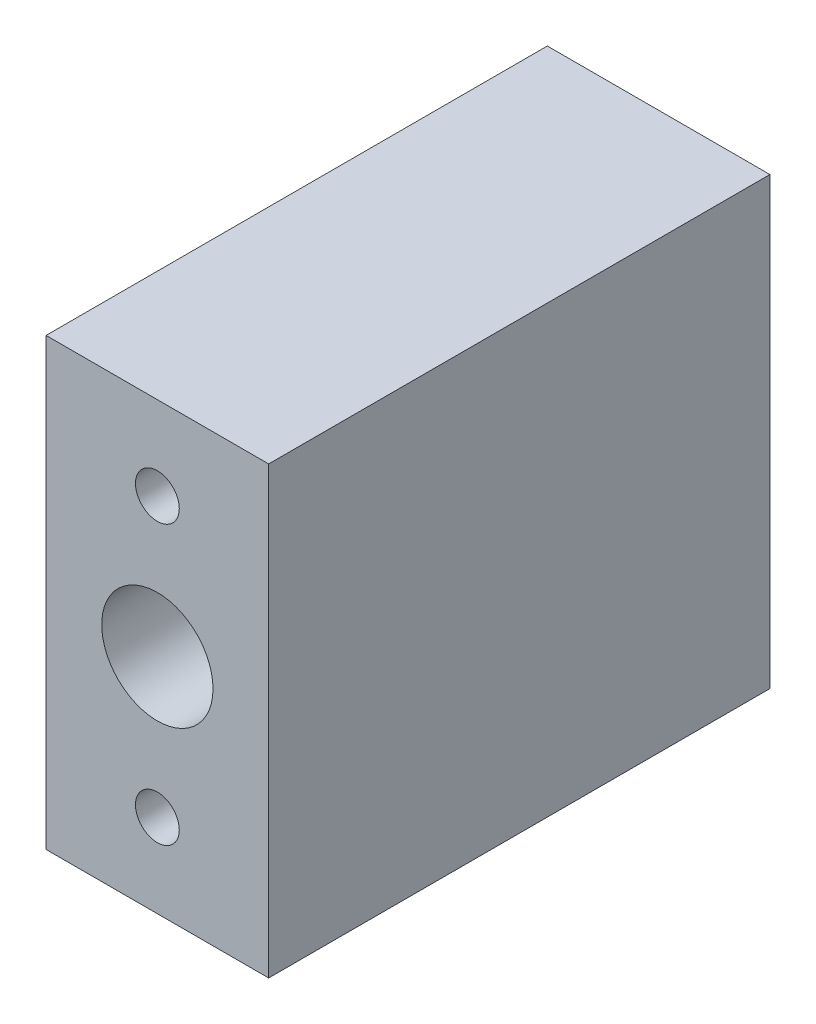
SolidWorks part; units mm, degrees
ref_plane "Front" through (0, 0, 0) normal (0, 0, 1) x (1, 0, 0)
ref_plane "Top" through (0, 0, 0) normal (0, 1, 0) x (1, 0, 0)
ref_plane "Right" through (0, 0, 0) normal (1, 0, 0) x (0, 0, -1)
sketch "Sketch1" plane through (0, 0, 0) normal (0, 1, 0) x (1, 0, 0)
  line L0 (0, 28.5986) -> (-12.7, 28.5986)
  line L1 (0, 0) -> (64, 0)
  line L2 (0, 0) -> (0, 28.5986)
  line L3 (0, 28.5986) -> (64, 28.5986)
  line L4 (64, 0) -> (64, 28.5986)
  line L5 (0, 0) -> (-12.7, 0)
  line L6 (-12.7, 0) -> (-12.7, 28.5986)
  dimension "D1" = 64
  dimension "D2" = 28.5986
  dimension "D3" = 12.7
extrude "Boss-Extrude1" add sketch "Sketch1" along normal blind 25.4 contours L6 L5 L2 L0
sketch "Sketch2" plane through (0, 0, 0) normal (0, 0, 1) x (1, 0, 0)
  line L0 (-6.35, 25.4) -> (-6.35, 20.6375)
  line L3 (0, 25.4) -> (-12.7, 25.4) construction
  line L4 (-6.35, 0) -> (-6.35, 4.7625)
  line L5 (0, 0) -> (-12.7, 0) construction
  circle A0 centre (-6.35, 12.7) radius 3.175
  circle A1 centre (-6.35, 20.6375) radius 1.25
  circle A2 centre (-6.35, 4.7625) radius 1.25
  dimension "D1" = 4.7625
  dimension "D2" = 4.7625
extrude "Cut-Extrude1" cut sketch "Sketch2" against normal through all
